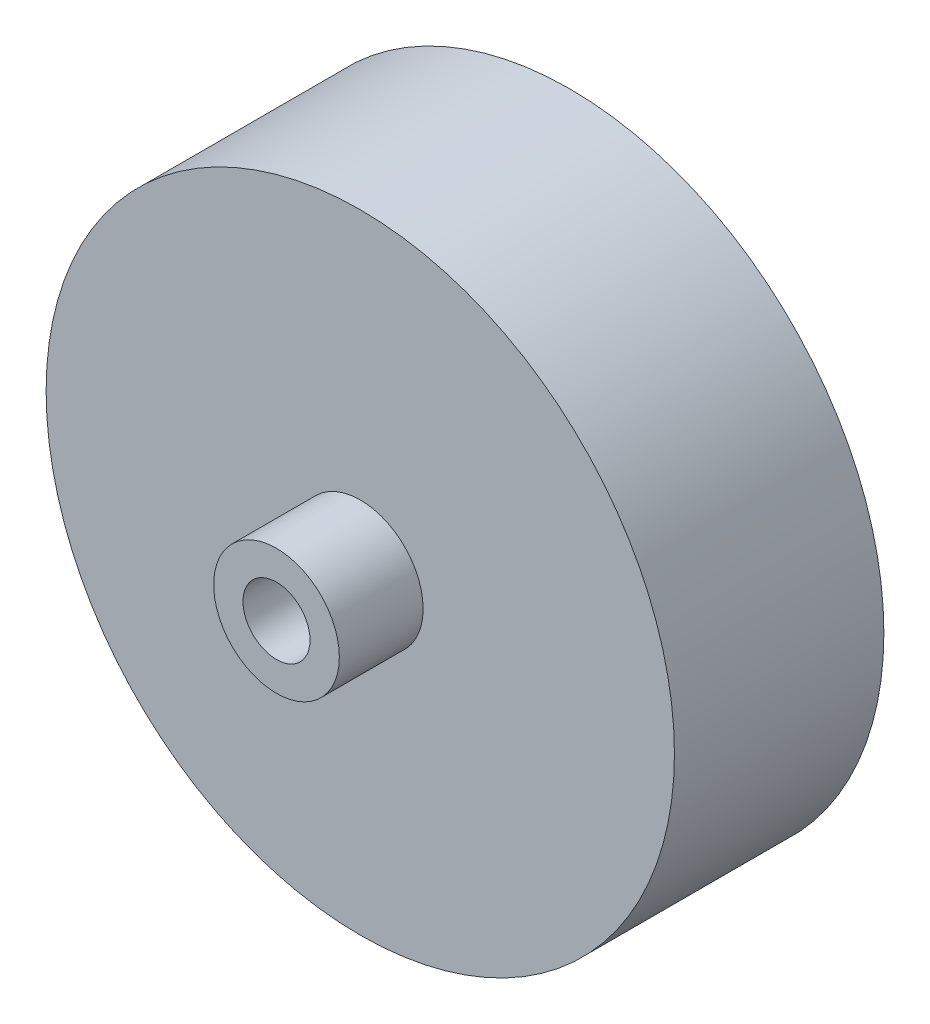
SolidWorks part; units mm, degrees
ref_plane "Front Plane" through (0, 0, 0) normal (0, 0, 1) x (1, 0, 0)
ref_plane "Top Plane" through (0, 0, 0) normal (0, 1, 0) x (1, 0, 0)
ref_plane "Right Plane" through (0, 0, 0) normal (1, 0, 0) x (0, 0, -1)
sketch "Sketch1" plane through (0, 0, 0) normal (0, 0, 1) x (1, 0, 0)
  circle A0 centre (0, 0) radius 37.5
  dimension "D1" = 75
extrude "Boss-Extrude1" add sketch "Sketch1" along normal blind 25
sketch "Sketch2" plane through (0, 0, 25) normal (0, 0, 1) x (1, 0, 0)
  circle A0 centre (0, 0) radius 7.5
  circle A1 centre (0, 0) radius 4
  dimension "D1" = 15
  dimension "D2" = 8
extrude "Boss-Extrude2" add sketch "Sketch2" along normal blind 10
